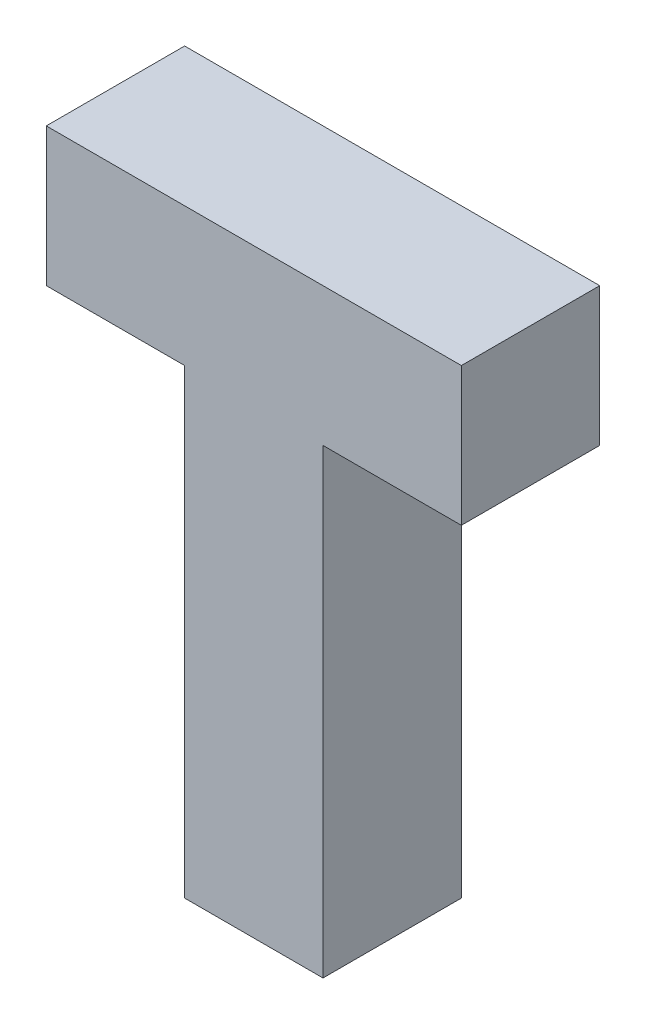
SolidWorks part; units mm, degrees
material "Acrylic (Medium-high impact)"
ref_plane "Alzado" through (0, 0, 0) normal (0, 0, 1) x (1, 0, 0)
ref_plane "Planta" through (0, 0, 0) normal (0, 1, 0) x (1, 0, 0)
ref_plane "Vista lateral" through (0, 0, 0) normal (1, 0, 0) x (0, 0, -1)
sketch "Sketch1" plane through (0, 0, 0) normal (0, 0, 1) x (1, 0, 0)
  line L6 (-2.2048, 6.3617) -> (-2.2048, 3.3617)
  line L7 (-2.2048, 3.3617) -> (0.7952, 3.3617)
  line L8 (0.7952, 3.3617) -> (0.7952, -6.6383)
  line L9 (0.7952, -6.6383) -> (3.7952, -6.6383)
  line L10 (3.7952, -6.6383) -> (3.7952, 3.3617)
  line L11 (3.7952, 3.3617) -> (6.7952, 3.3617)
  line L12 (6.7952, 3.3617) -> (6.7952, 6.3617)
  line L14 (-2.2048, 6.3617) -> (6.7952, 6.3617)
  dimension "D1" = 9
  dimension "D2" = 3
  dimension "D3" = 3
extrude "Boss-Extrude1" add sketch "Sketch1" along normal blind 3
